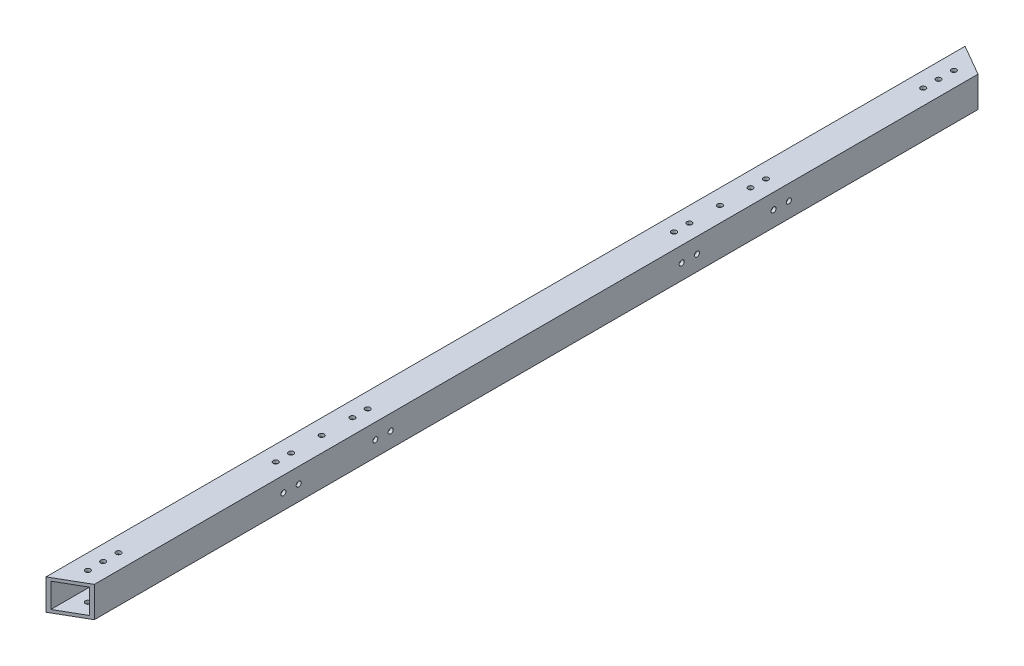
SolidWorks part; units mm, degrees
ref_plane "前视基准面" through (0, 0, 0) normal (0, 0, 1) x (1, 0, 0)
ref_plane "上视基准面" through (0, 0, 0) normal (0, 1, 0) x (1, 0, 0)
ref_plane "右视基准面" through (0, 0, 0) normal (1, 0, 0) x (0, 0, -1)
other "Configuration Table"
sketch "草图1" plane through (0, 0, 0) normal (0, 0, 1) x (1, 0, 0)
  line L1 (-8, -8) -> (8, -8)
  line L2 (-8, -8) -> (-8, 8)
  line L3 (-8, 8) -> (8, 8)
  line L4 (8, -8) -> (8, 8)
  line L5 (-8, -8) -> (8, 8) construction
  line L6 (-8, 8) -> (8, -8) construction
  line L7 (-10, -10) -> (10, -10)
  line L8 (-10, -10) -> (-10, 10)
  line L9 (-10, 10) -> (10, 10)
  line L10 (10, -10) -> (10, 10)
  line L11 (-10, -10) -> (10, 10) construction
  line L12 (-10, 10) -> (10, -10) construction
  point P0 (0, 0)
  point P6 (0, 0)
  dimension "D1" = 20
  dimension "D2" = 2
  dimension "D3" = 2
  dimension "D4" = 20
extrude "凸台-拉伸1" add sketch "草图1" along normal blind 600
sketch "草图2" plane through (0, 10, 0) normal (0, 1, 0) x (1, 0, 0)
  line L0 (-10, 0) -> (10, -11.547)
  line L1 (10, -600) -> (10, 0) construction
  line L2 (10, -11.547) -> (10, 0)
  line L3 (10, 0) -> (-10, 0)
  line L4 (-10, -300) -> (10, -300) construction
  line L5 (-10, -600) -> (-10, 0) construction
  line L6 (10, -600) -> (-10, -600)
  line L7 (10, -588.453) -> (10, -600)
  line L8 (-10, -600) -> (10, -588.453)
  dimension "D1" = 120
extrude "切除-拉伸1" cut sketch "草图2" against normal mid plane 600
sketch "草图3" plane through (0, 10, 0) normal (0, 1, 0) x (1, 0, 0)
  line L0 (-10, -17.3183) -> (10, -17.3183) construction
  line L1 (-10, -600) -> (-10, 0) construction
  line L2 (10, -588.453) -> (10, -11.547) construction
  line L3 (-10, -300) -> (10, -300) construction
  line L4 (10, -11.547) -> (-10, 0) construction
  circle A0 centre (0, -17.3183) radius 1.65
  circle A1 centre (0, -582.6817) radius 1.65
  circle A2 centre (0, -27.3183) radius 1.65
  circle A3 centre (0, -37.3183) radius 1.65
  circle A4 centre (0, -562.6817) radius 1.65
  circle A5 centre (0, -572.6817) radius 1.65
  point P11 (0, -582.6817)
  dimension "D2" = 3.3
  dimension "D1" = 9.9981
  dimension "D3" = 10
  dimension "D4" = 10
extrude "切除-拉伸2" cut sketch "草图3" against normal mid plane 600
sketch "草图4" plane through (0, 0, 0) normal (0, 1, 0) x (1, 0, 0)
  line L0 (0, -17.3183) -> (0, -582.6817) construction
  circle A0 centre (0, -169.9983) radius 1.65
  circle A1 centre (0, -429.9983) radius 1.65
  circle A2 centre (0, -149.9983) radius 1.65
  circle A3 centre (0, -189.9983) radius 1.65
  circle A4 centre (0, -409.9983) radius 1.65
  circle A5 centre (0, -449.9983) radius 1.65
  circle A6 centre (0, -199.9983) radius 1.65
  circle A7 centre (0, -139.9983) radius 1.65
  circle A8 centre (0, -459.9983) radius 1.65
  circle A9 centre (0, -399.9983) radius 1.65
  dimension "D3" = 3.3
  dimension "D4" = 3.3
  dimension "D9" = 3.3
  dimension "D10" = 3.3
  dimension "D13" = 3.3
  dimension "D14" = 3.3
  dimension "D1" = 260
  dimension "D2" = 152.68
  dimension "D5" = 20
  dimension "D6" = 20
  dimension "D7" = 20
  dimension "D8" = 20
  dimension "D11" = 10
  dimension "D12" = 10
  dimension "D15" = 10
  dimension "D16" = 10
extrude "切除-拉伸3" cut sketch "草图4" against normal mid plane 20
sketch "草图6" plane through (-10, 0, 0) normal (-1, 0, 0) x (0, 0, 1)
  line L0 (0, 0) -> (170, 0) construction
  line L1 (300, -10) -> (300, 10) construction
  line L2 (600, -10) -> (0, -10) construction
  line L3 (600, 10) -> (0, 10) construction
  circle A1 centre (195, 0) radius 1.65
  circle A2 centre (145, 0) radius 1.65
  circle A3 centre (205, 0) radius 1.65
  circle A4 centre (135, 0) radius 1.65
  circle A5 centre (465, 0) radius 1.65
  circle A6 centre (395, 0) radius 1.65
  circle A7 centre (455, 0) radius 1.65
  circle A8 centre (405, 0) radius 1.65
  dimension "D3" = 3.3
  dimension "D4" = 3.3
  dimension "D7" = 3.3
  dimension "D8" = 3.3
  dimension "D1" = 170
  dimension "D5" = 25
  dimension "D6" = 25
  dimension "D9" = 10
  dimension "D10" = 10
extrude "切除-拉伸4" cut sketch "草图6" against normal through all
